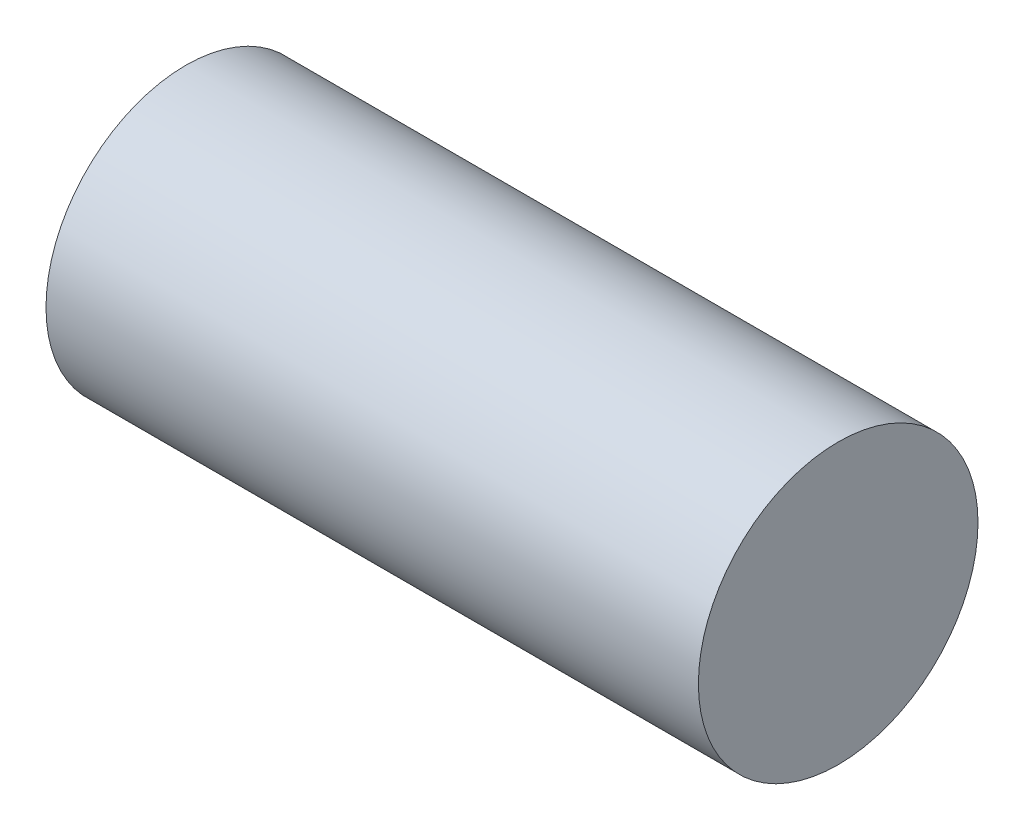
SolidWorks part; units mm, degrees
ref_plane "Front Plane" through (0, 0, 0) normal (0, 0, 1) x (1, 0, 0)
ref_plane "Top Plane" through (0, 0, 0) normal (0, 1, 0) x (1, 0, 0)
ref_plane "Right Plane" through (0, 0, 0) normal (1, 0, 0) x (0, 0, -1)
sketch "Sketch3" plane through (0, 0, 0) normal (1, 0, 0) x (0, 0, -1)
  circle A0 centre (0, 0) radius 15
  dimension "D1" = 30
extrude "Boss-Extrude1" add sketch "Sketch3" along normal blind 70
ref_plane "Düzlem2" through (65, 0, 0) normal (1, 0, 0) x (0, 0, -1)
sketch "Çizim2" plane through (65, 0, 0) normal (1, 0, 0) x (0, 0, -1)
  circle A0 centre (0, 0) radius 12.5
  dimension "D1" = 25
extrude "Kes-Ekstrüzyon1" cut sketch "Çizim2" against normal blind 60
